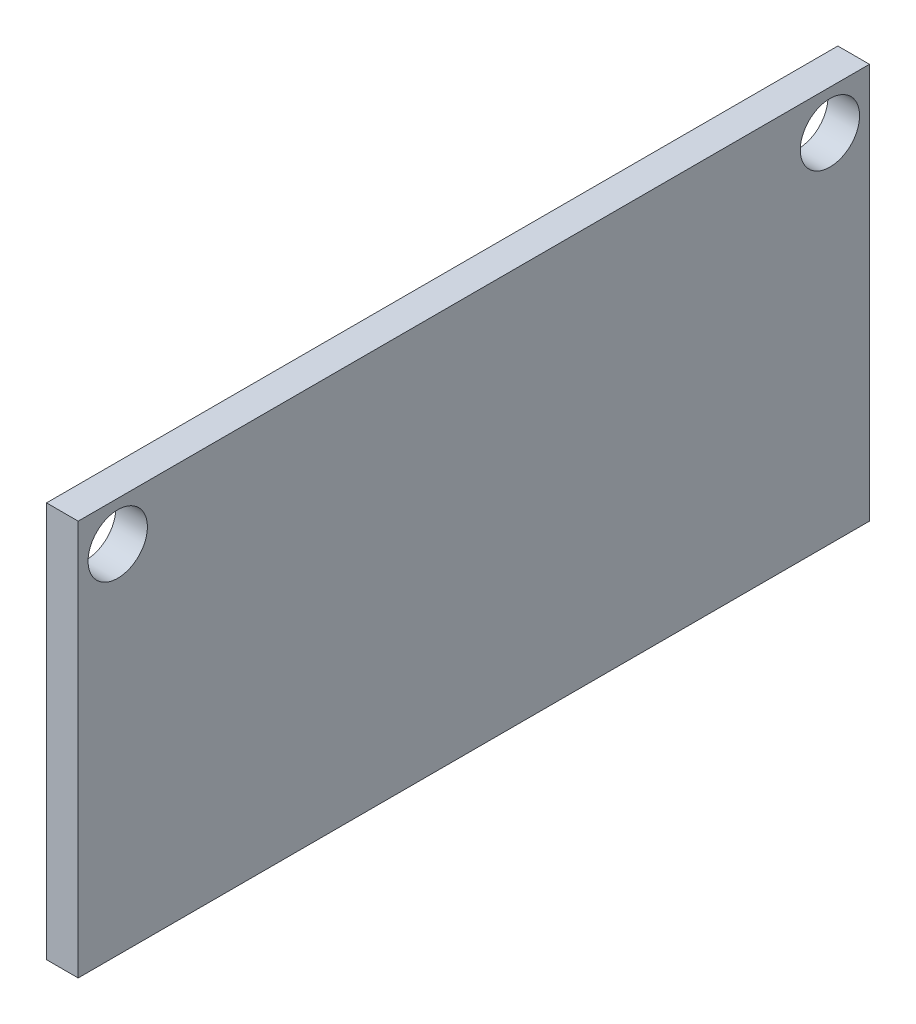
SolidWorks part; units mm, degrees
ref_plane "Plan de face" through (0, 0, 0) normal (0, 0, 1) x (1, 0, 0)
ref_plane "Plan de dessus" through (0, 0, 0) normal (0, 1, 0) x (1, 0, 0)
ref_plane "Plan de droite" through (0, 0, 0) normal (1, 0, 0) x (0, 0, -1)
sketch "Esquisse1" plane through (0, 0, 0) normal (1, 0, 0) x (0, 0, -1)
  line L0 (0, 0) -> (0, 20) construction
  line L1 (-20, 0) -> (20, 0)
  line L2 (-20, 0) -> (-20, 20)
  line L3 (-20, 20) -> (20, 20)
  line L4 (20, 0) -> (20, 20)
  circle A0 centre (-18, 18) radius 1.5
  circle A1 centre (18, 18) radius 1.5
  point P4 (0, 0)
  dimension "D3" = 3
  dimension "D1" = 20
  dimension "D2" = 40
  dimension "D4" = 2
  dimension "D5" = 2
extrude "Extrusion1" add sketch "Esquisse1" along normal blind 1.6
